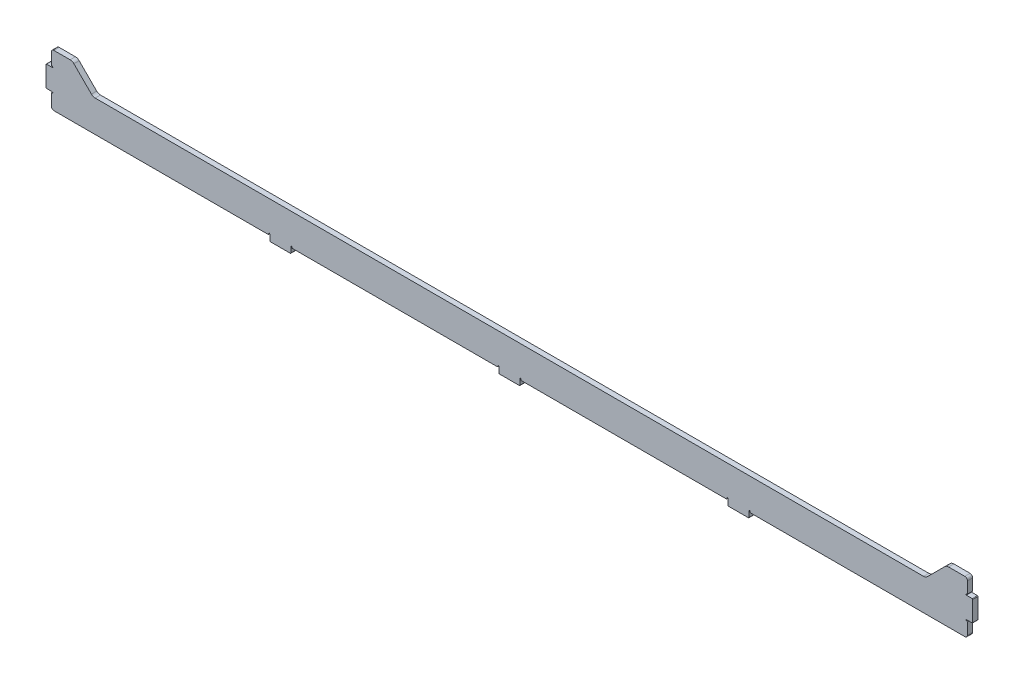
SolidWorks part; units mm, degrees
material "6061-T6 (SS)"
ref_plane "Front Plane" through (0, 0, 0) normal (0, 0, 1) x (1, 0, 0)
ref_plane "Top Plane" through (0, 0, 0) normal (0, 1, 0) x (1, 0, 0)
ref_plane "Right Plane" through (0, 0, 0) normal (1, 0, 0) x (0, 0, -1)
sketch "Sketch1" plane through (0, 0, 0) normal (0, 0, 1) x (1, 0, 0)
  line L0 (-276.225, 0) -> (276.225, 0)
  line L1 (-276.225, 0) -> (-276.225, 31.496)
  line L2 (276.225, 0) -> (276.225, 31.496)
  line L3 (276.225, 31.496) -> (263.525, 31.496)
  line L4 (263.525, 31.496) -> (251.079, 19.05)
  line L5 (251.079, 19.05) -> (-251.079, 19.05)
  line L6 (-263.525, 31.496) -> (-251.079, 19.05)
  line L7 (-263.525, 31.496) -> (-276.225, 31.496)
  point P3 (0, 0)
  dimension "D1" = 31.496
  dimension "D2" = 552.45
  dimension "D3" = 12.7
  dimension "D4" = 19.05
  dimension "D5" = 135
  dimension "D6" = 135
extrude "Boss-Extrude1" add sketch "Sketch1" along normal blind 3.175
fillet "Fillet1" radius 3.175 4 edges at (251.079, 19.05, 1.5875) (263.525, 31.496, 1.5875) (-251.079, 19.05, 1.5875) (-263.525, 31.496, 1.5875)
fillet "Fillet2" radius 1.5875 4 edges at (276.225, 31.496, 1.5875) (276.225, 0, 1.5875) (-276.225, 0, 1.5875) (-276.225, 31.496, 1.5875)
sketch "Sketch3" plane through (0, 0, 3.175) normal (0, 0, 1) x (1, 0, 0)
  line L0 (276.225, 1.5875) -> (276.225, 29.9085) construction
  line L1 (276.225, 22.098) -> (279.4, 22.098)
  line L2 (276.225, 22.098) -> (276.225, 9.398)
  line L3 (276.225, 9.398) -> (279.4, 9.398)
  line L4 (279.4, 22.098) -> (279.4, 9.398)
  line L5 (-274.6375, 0) -> (274.6375, 0) construction
  line L6 (131.7625, 0) -> (144.4625, 0)
  line L7 (131.7625, 0) -> (131.7625, -3.175)
  line L8 (131.7625, -3.175) -> (144.4625, -3.175)
  line L9 (144.4625, 0) -> (144.4625, -3.175)
  line L11 (0, 0) -> (6.35, 0)
  line L12 (0, 0) -> (0, -3.175)
  line L13 (0, -3.175) -> (6.35, -3.175)
  line L14 (6.35, 0) -> (6.35, -3.175)
  point P6 (276.225, 15.748)
  point P7 (276.225, 15.748)
  point P19 (138.1125, 0)
  dimension "D1" = 3.175
  dimension "D2" = 12.7
  dimension "D3" = 6.35
  dimension "D4" = 12.7
  dimension "D5" = 138.1125
extrude "Boss-Extrude2" add sketch "Sketch3" against normal up to surface (3.175 mm away) up to face at (0, 20.5105, 0)
mirror "Mirror1" about plane through (0, 0, 0) normal (1, 0, 0) of "Boss-Extrude2"
sketch "Sketch4" plane through (0, 0, 3.175) normal (0, 0, 1) x (1, 0, 0)
  line L0 (-276.225, 22.4155) -> (-275.59, 22.4155) construction
  line L1 (-276.225, 29.9085) -> (-276.225, 22.098) construction
  line L2 (-276.225, 22.733) -> (-275.59, 22.733)
  line L3 (-276.225, 22.098) -> (-275.59, 22.098)
  line L4 (-279.4, 22.098) -> (-276.225, 22.098) construction
  line L5 (-276.225, 9.0805) -> (-275.59, 9.0805) construction
  line L6 (-276.225, 9.398) -> (-276.225, 1.5875) construction
  line L7 (-276.225, 9.398) -> (-275.59, 9.398)
  line L8 (-276.225, 8.763) -> (-275.59, 8.763)
  line L9 (-276.225, 9.398) -> (-279.4, 9.398) construction
  line L10 (-144.78, 0) -> (-144.78, 0.635) construction
  line L11 (-274.6375, 0) -> (-144.4625, 0) construction
  line L12 (-145.0975, 0) -> (-145.0975, 0.635)
  line L13 (-144.4625, 0) -> (-144.4625, 0.635)
  line L14 (-131.445, 0.635) -> (-131.445, 0) construction
  line L15 (-131.7625, 0) -> (-6.35, 0) construction
  line L16 (-131.1275, 0.635) -> (-131.1275, 0)
  line L17 (-131.7625, 0.635) -> (-131.7625, 0)
  line L18 (-6.6675, 0) -> (-6.6675, 0.635) construction
  line L19 (-6.985, 0) -> (-6.985, 0.635)
  line L20 (-6.35, 0) -> (-6.35, 0.635)
  line L21 (-6.35, -3.175) -> (-6.35, 0) construction
  line L22 (-131.7625, 0) -> (-131.7625, -3.175) construction
  line L23 (-144.4625, -3.175) -> (-144.4625, 0) construction
  arc A0 (-276.225, 22.733) -> (-276.225, 22.098) centre (-276.225, 22.4155) ccw
  arc A1 (-275.59, 22.098) -> (-275.59, 22.733) centre (-275.59, 22.4155) ccw
  arc A2 (-276.225, 9.398) -> (-276.225, 8.763) centre (-276.225, 9.0805) ccw
  arc A3 (-275.59, 8.763) -> (-275.59, 9.398) centre (-275.59, 9.0805) ccw
  arc A4 (-145.0975, 0) -> (-144.4625, 0) centre (-144.78, 0) ccw
  arc A5 (-144.4625, 0.635) -> (-145.0975, 0.635) centre (-144.78, 0.635) ccw
  arc A6 (-131.1275, 0.635) -> (-131.7625, 0.635) centre (-131.445, 0.635) ccw
  arc A7 (-131.7625, 0) -> (-131.1275, 0) centre (-131.445, 0) ccw
  arc A8 (-6.985, 0) -> (-6.35, 0) centre (-6.6675, 0) ccw
  arc A9 (-6.35, 0.635) -> (-6.985, 0.635) centre (-6.6675, 0.635) ccw
  point P4 (-275.9075, 22.4155)
  point P15 (-275.9075, 9.0805)
  point P26 (-144.78, 0.3175)
  point P31 (-131.445, 0.3175)
  point P40 (-6.6675, 0.3175)
  dimension "D1" = 0.3175
  dimension "D2" = 0.635
extrude "Cut-Extrude1" cut sketch "Sketch4" against normal through all
mirror "Mirror2" about plane through (0, 0, 0) normal (1, 0, 0) of "Cut-Extrude1"
fillet "Fillet3" radius 0.3175 20 edges at (-276.225, 22.733, 1.5875) (-279.4, 22.098, 1.5875) (-279.4, 9.398, 1.5875) (-276.225, 8.763, 1.5875) (-145.0975, 0, 1.5875) (-144.4625, -3.175, 1.5875) (-131.7625, -3.175, 1.5875) (-131.1275, 0, 1.5875) (-6.35, -3.175, 1.5875) (-6.985, 0, 1.5875) (6.985, 0, 1.5875) (6.35, -3.175, 1.5875) (131.1275, 0, 1.5875) (131.7625, -3.175, 1.5875) (145.0975, 0, 1.5875) (144.4625, -3.175, 1.5875) (279.4, 22.098, 1.5875) (279.4, 9.398, 1.5875) (276.225, 8.763, 1.5875) (276.225, 22.733, 1.5875)
